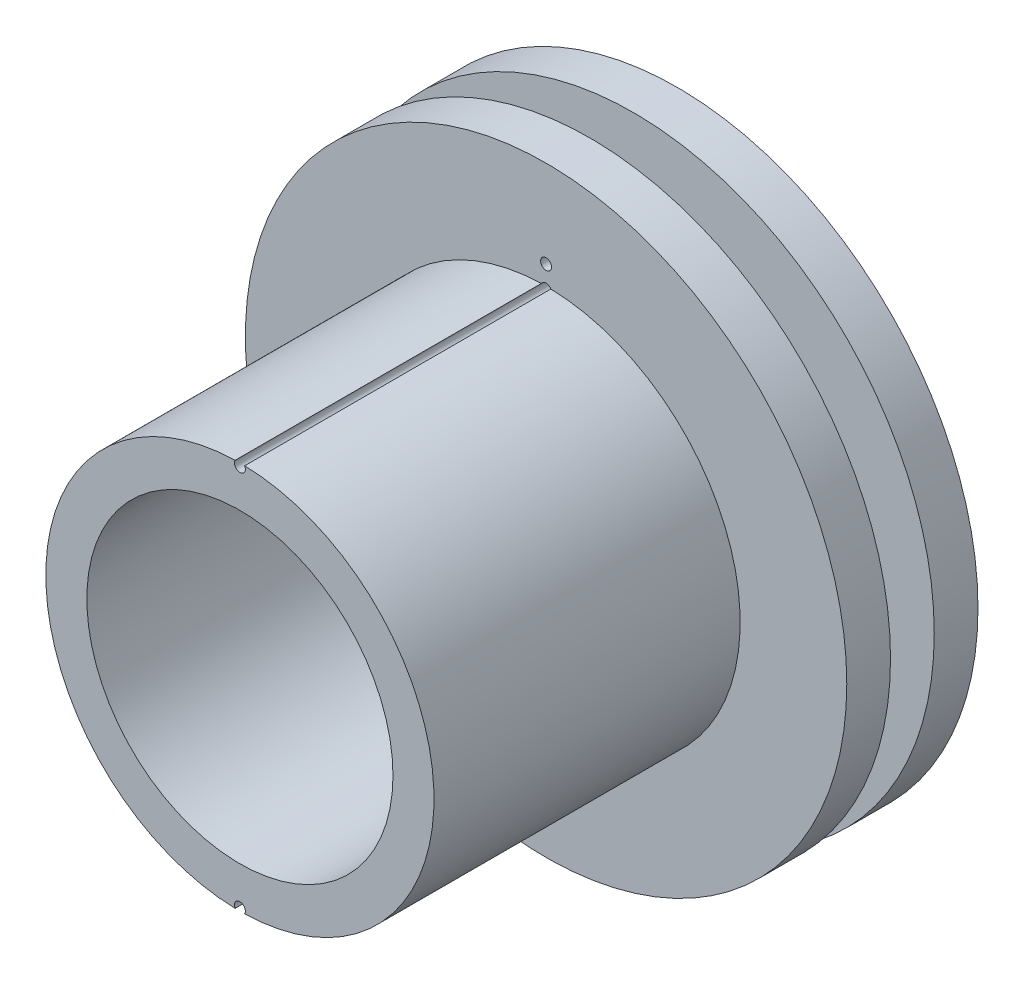
SolidWorks part; units mm, degrees
material "ABS"
ref_plane "Front Plane" through (0, 0, 0) normal (0, 0, 1) x (1, 0, 0)
ref_plane "Top Plane" through (0, 0, 0) normal (0, 1, 0) x (1, 0, 0)
ref_plane "Right Plane" through (0, 0, 0) normal (1, 0, 0) x (0, 0, -1)
sketch "Sketch1" plane through (0, 0, 0) normal (0, 0, 1) x (1, 0, 0)
  circle A0 centre (0, 0) radius 13.75
  dimension "D1" = 27.5
extrude "Boss-Extrude1" add sketch "Sketch1" along normal blind 2
sketch "Sketch2" plane through (0, 0, 0) normal (0, 0, 1) x (1, 0, 0)
  circle A0 centre (0, 0) radius 8.5
  dimension "D1" = 17
extrude "Boss-Extrude2" add sketch "Sketch2" along normal blind 6
sketch "Sketch3" plane through (0, 0, 0) normal (0, 0, 1) x (1, 0, 0)
  circle A0 centre (0, 0) radius 13.75
  dimension "D1" = 27.5
extrude "Boss-Extrude3" add sketch "Sketch3" along normal blind 2 from offset 4
sketch "Sketch5" plane through (0, 0, 0) normal (0, 0, 1) x (1, 0, 0)
  circle A0 centre (0, 0) radius 7
extrude "Cut-Extrude2" cut sketch "Sketch5" along normal through all
sketch "Sketch6" plane through (0, 0, 0) normal (0, 0, 1) x (1, 0, 0)
  circle A0 centre (0, 0) radius 7
  circle A1 centre (0, 0) radius 8.875
  dimension "D1" = 17.75
extrude "Boss-Extrude4" add sketch "Sketch6" along normal blind 14 from surface at 6 starting at face at (13.75, 0, 6)
sketch "Sketch9" plane through (0, 0, 0) normal (0, 0, 1) x (1, 0, 0)
  circle A0 centre (0, 9.75) radius 0.25
  circle A1 centre (0, -9.75) radius 0.25
  circle A2 centre (0, 8.75) radius 0.25
  circle A3 centre (0, -8.75) radius 0.25
extrude "Cut-Extrude3" cut sketch "Sketch9" along normal through all from surface at 4 starting at face at (13.75, 0, 4)
